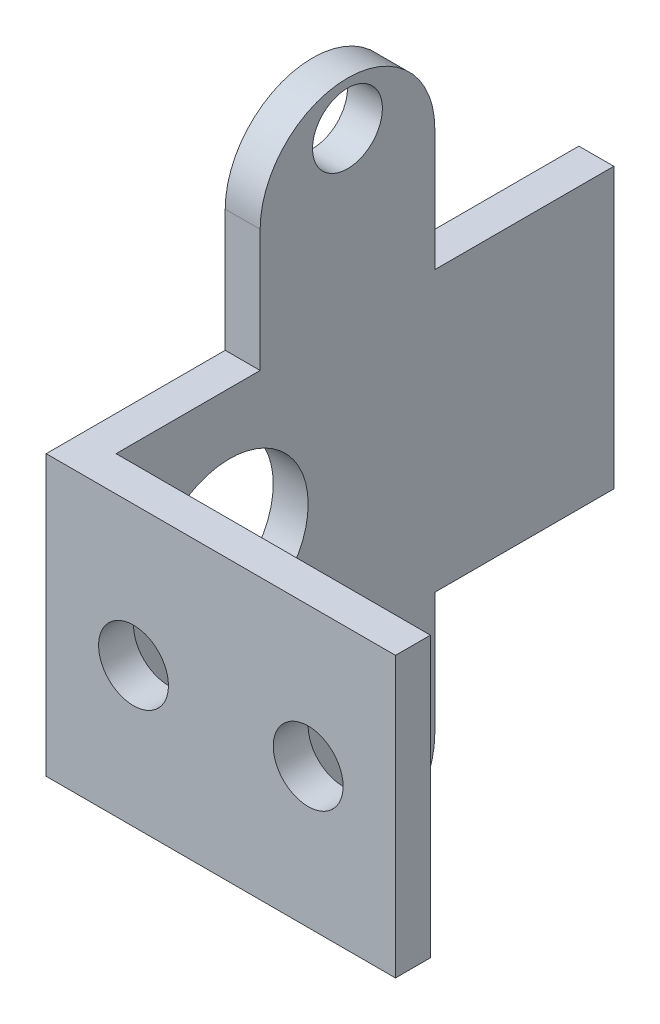
SolidWorks part; units mm, degrees
ref_plane "Front Plane" through (0, 0, 0) normal (0, 0, 1) x (1, 0, 0)
ref_plane "Top Plane" through (0, 0, 0) normal (0, 1, 0) x (1, 0, 0)
ref_plane "Right Plane" through (0, 0, 0) normal (1, 0, 0) x (0, 0, -1)
sketch "Sketch1" plane through (0, 0, 0) normal (0, 1, 0) x (1, 0, 0)
  line L0 (-17.9227, 12.5249) -> (-17.9227, -17.9751)
  line L1 (-17.9227, 12.5249) -> (-15.9227, 12.5249)
  line L4 (-15.9227, 12.5249) -> (-15.9227, -15.9751)
  line L5 (-15.9227, -15.9751) -> (2.0773, -15.9751)
  line L7 (-17.9227, -17.9751) -> (2.0773, -17.9751)
  line L8 (2.0773, -15.9751) -> (2.0773, -17.9751)
  dimension "D1" = 30.5
  dimension "D2" = 20
  dimension "D3" = 2
  dimension "D4" = 2
extrude "Boss-Extrude1" add sketch "Sketch1" along normal blind 16
sketch "Sketch4" plane through (0, 0, 17.9751) normal (0, 0, 1) x (1, 0, 0)
  line L0 (-17.9227, 0) -> (2.0773, 0) construction
  line L1 (2.0773, 16) -> (2.0773, 0) construction
  circle A0 centre (-12.9227, 8) radius 2
  circle A1 centre (-2.9227, 8) radius 2
  dimension "D5" = 4
  dimension "D6" = 4
  dimension "D1" = 8
  dimension "D2" = 8
  dimension "D3" = 10
  dimension "D4" = 5
extrude "Cut-Extrude1" cut sketch "Sketch4" against normal blind 16
sketch "Sketch6" plane through (0, 0, 0) normal (0, -1, 0) x (1, 0, 0)
  line L0 (-17.9227, -12.5249) -> (-17.9227, 17.9751) construction
  line L1 (-17.9227, 7.7251) -> (-15.9227, 7.7251)
  line L2 (-17.9227, 7.7251) -> (-17.9227, -2.2749)
  line L3 (-17.9227, -2.2749) -> (-15.9227, -2.2749)
  line L4 (-15.9227, 7.7251) -> (-15.9227, -2.2749)
  line L5 (-15.9227, 15.9751) -> (-15.9227, -12.5249) construction
  line L6 (-15.9227, -12.5249) -> (-17.9227, -12.5249) construction
  point P10 (-16.9227, 7.7251)
  dimension "D1" = 10.25
  dimension "D2" = 10
extrude "Boss-Extrude2" add sketch "Sketch6" along normal blind 12
sketch "Sketch7" plane through (-15.9227, 0, 0) normal (1, 0, 0) x (0, 0, -1)
  line L0 (2.2749, -12) -> (-7.7251, -12) construction
  line L1 (-7.7251, -12) -> (-7.7251, 0) construction
  line L2 (-11.1713, -12.363) -> (4.9293, -12.363)
  line L5 (-11.1713, -7) -> (-11.1713, -12.363)
  line L10 (4.9293, -12.363) -> (4.9293, -7)
  line L11 (4.9293, -7) -> (2.2749, -7)
  line L12 (-11.1713, -7) -> (-7.7251, -7)
  arc A0 (-7.7251, -7) -> (2.2749, -7) centre (-2.7251, -7) ccw
  dimension "D1" = 10
extrude "Cut-Extrude2" cut sketch "Sketch7" against normal blind 12
sketch "Sketch8" plane through (-15.9227, 0, 0) normal (1, 0, 0) x (0, 0, -1)
  line L0 (-15.9751, 16) -> (12.5249, 16) construction
  line L1 (2.2749, -7) -> (2.2749, 0) construction
  circle A0 centre (-2.7251, -9.5) radius 2
  arc A1 (-7.7251, -7) -> (2.2749, -7) centre (-2.7251, -7) ccw construction
  dimension "D1" = 4
  dimension "D2" = 25.5
  dimension "D3" = 5
extrude "Cut-Extrude3" cut sketch "Sketch8" against normal blind 12
ref_plane "Plane1" through (0, 8, 0) normal (0, -1, 0) x (-1, 0, 0)
mirror "Mirror1" about plane through (0, 8, 0) normal (0, -1, 0) of "Boss-Extrude2", "Cut-Extrude3", "Cut-Extrude2"
sketch "Sketch9" plane through (-15.9227, 0, 0) normal (1, 0, 0) x (0, 0, -1)
  line L0 (12.5249, 16) -> (12.5249, 0) construction
  line L1 (-15.9751, 0) -> (-7.7251, 0) construction
  line L2 (-17.9751, 16) -> (-17.9751, 0) construction
  circle A0 centre (-9.4751, 8) radius 4.5
  point P6 (-11.8501, 0)
  dimension "D3" = 9
  dimension "D1" = 22
  dimension "D2" = 8
  dimension "D4" = 8.5
extrude "Cut-Extrude4" cut sketch "Sketch9" against normal blind 12
